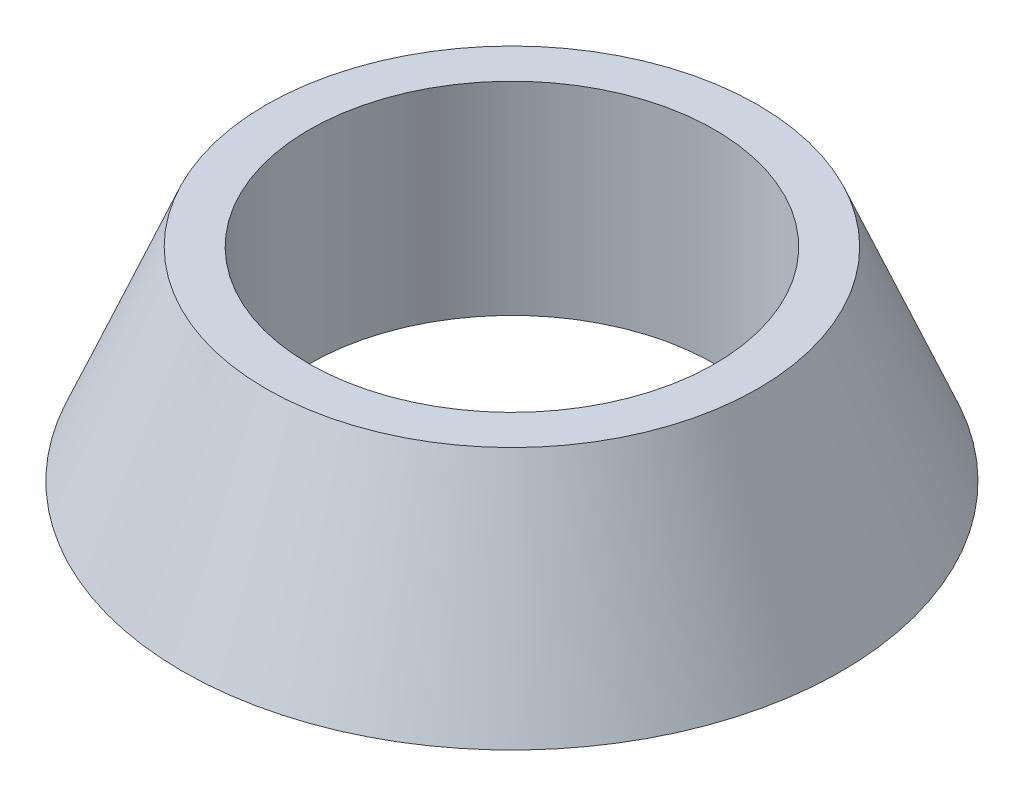
SolidWorks part; units mm, degrees
material "1.0545 (S355N)"
ref_plane "Płaszczyzna przednia" through (0, 0, 0) normal (0, 0, 1) x (1, 0, 0)
ref_plane "Płaszczyzna górna" through (0, 0, 0) normal (0, 1, 0) x (1, 0, 0)
ref_plane "Płaszczyzna prawa" through (0, 0, 0) normal (1, 0, 0) x (0, 0, -1)
sketch "Szkic1" plane through (0, 0, 0) normal (0, 0, 1) x (1, 0, 0)
  line L0 (8, 4) -> (8, -4)
  line L1 (8, -4) -> (13, -4)
  line L2 (13, -4) -> (9.7, 4)
  line L3 (9.7, 4) -> (8, 4)
  line L4 (0, 7.9207) -> (0, -9.5499) construction
  point P2 (8, 0)
  dimension "D1" = 8
  dimension "D2" = 9.7
  dimension "D3" = 13
  dimension "D4" = 8
revolve "Obrót1" add sketch "Szkic1" angle 360 about L4
